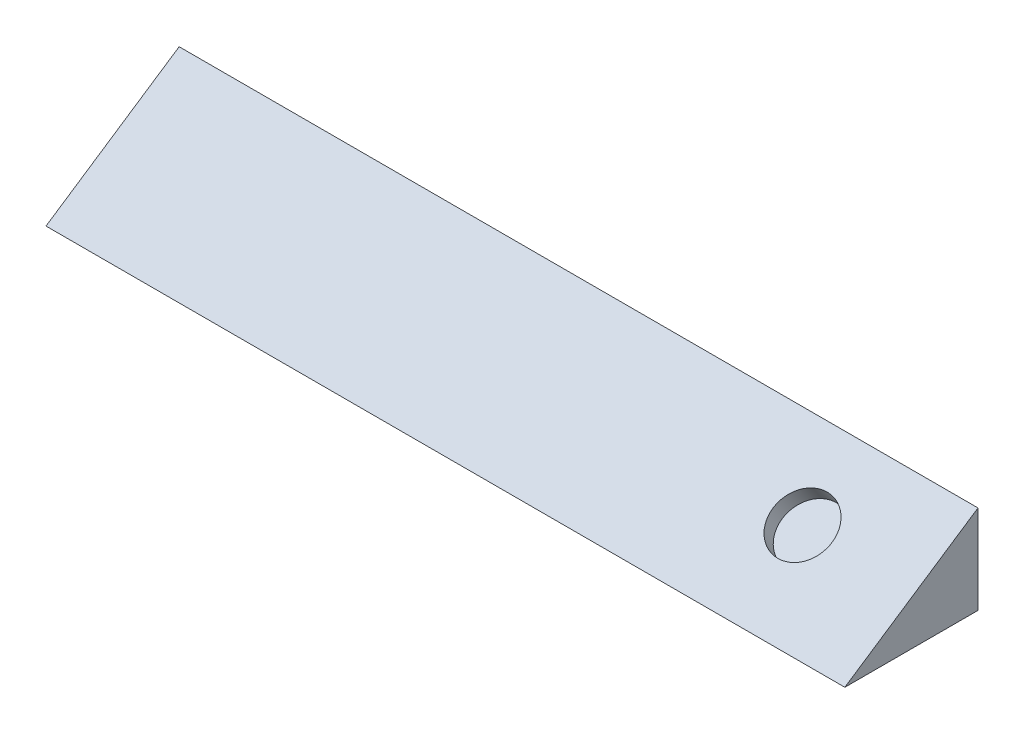
SolidWorks part; units mm, degrees
ref_plane "Front Plane" through (0, 0, 0) normal (0, 0, 1) x (1, 0, 0)
ref_plane "Top Plane" through (0, 0, 0) normal (0, 1, 0) x (1, 0, 0)
ref_plane "Right Plane" through (0, 0, 0) normal (1, 0, 0) x (0, 0, -1)
sketch "Sketch1" plane through (0, 0, 0) normal (1, 0, 0) x (0, 0, -1)
  line L0 (-20.4327, 83.1741) -> (-172.8327, -18.4259)
  line L1 (-20.4327, -18.4259) -> (-20.4327, 83.1741)
  line L2 (-172.8327, -18.4259) -> (-20.4327, -18.4259)
extrude "Boss-Extrude1" add sketch "Sketch1" along normal blind 914.4 contours L2 L1 L0
sketch "Sketch6" plane through (0, 67.0125, 44.675) normal (0, 0.8321, 0.5547) x (1, 0, 0)
  circle A0 centre (784.0786, -55.6442) radius 33.9023
extrude "Cut-Extrude1" cut sketch "Sketch6" against normal blind 19.05
